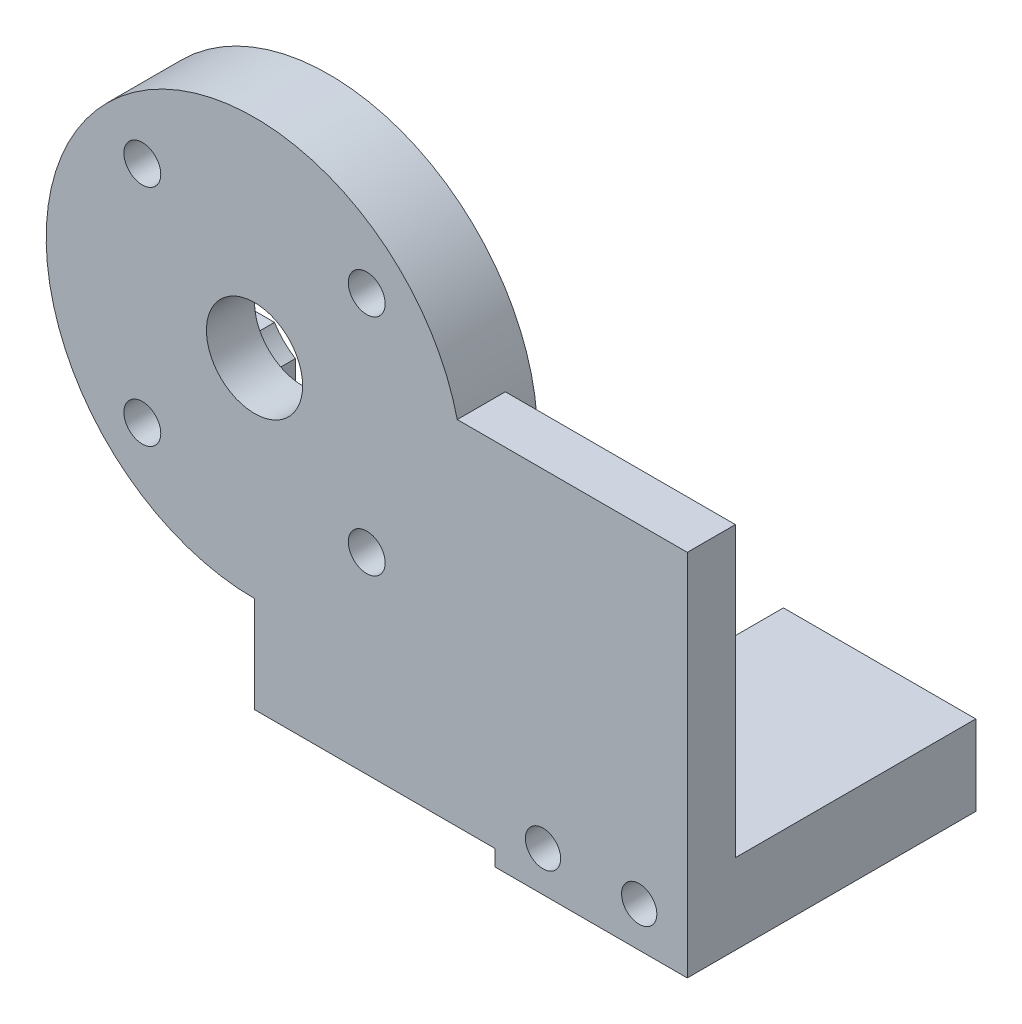
SolidWorks part; units mm, degrees
ref_plane "Front Plane" through (0, 0, 0) normal (0, 0, 1) x (1, 0, 0)
ref_plane "Top Plane" through (0, 0, 0) normal (0, 1, 0) x (1, 0, 0)
ref_plane "Right Plane" through (0, 0, 0) normal (1, 0, 0) x (0, 0, -1)
sketch "Stock_horn_attachment_profile" plane through (0, 0, 0) normal (0, 0, 1) x (1, 0, 0)
  circle A0 centre (0, 0) radius 13
  dimension "D1" = 26
extrude "Stock_horn_attachment" add sketch "Stock_horn_attachment_profile" along normal blind 3 from offset 15
sketch "Finger_arm_profile" plane through (0, 0, 0) normal (0, 0, 1) x (1, 0, 0)
  line L1 (0, -19) -> (27, -19)
  line L2 (0, -19) -> (0, 3)
  line L3 (0, 3) -> (27, 3)
  line L4 (27, -19) -> (27, 3)
  dimension "D1" = 27
  dimension "D2" = 22
extrude "Finger_arm" add sketch "Finger_arm_profile" along normal blind 3 from offset 15
sketch "Descending_contact_finger_profile" plane through (0, 0, 0) normal (0, 0, 1) x (1, 0, 0)
  line L1 (15, -20) -> (27, -20)
  line L2 (15, -20) -> (15, -15)
  line L3 (15, -15) -> (27, -15)
  line L4 (27, -20) -> (27, -15)
  dimension "D1" = 12
  dimension "D2" = 5
extrude "Descending_contact_finger" add sketch "Descending_contact_finger_profile" along normal blind 18
sketch "Horn_center_access_profile" plane through (0, 0, 0) normal (0, 0, 1) x (1, 0, 0)
  circle A0 centre (0, 0) radius 3
  dimension "D1" = 6
extrude "Horn_center_access" cut sketch "Horn_center_access_profile" along normal through all from offset 50
sketch "Captured_horn_key_boss_profile" plane through (0, 0, 0) normal (0, 0, 1) x (1, 0, 0)
  circle A0 centre (0, 0) radius 13
  dimension "D1" = 26
extrude "Captured_horn_key_boss" add sketch "Captured_horn_key_boss_profile" along normal blind 1.65 from offset 13.35
sketch "Stock_horn_pocket_Hub" plane through (0, 0, 0) normal (0, 0, 1) x (1, 0, 0)
  circle A0 centre (0, 0) radius 3.55
  dimension "D1" = 7.1
extrude "Key_pocket_Hub" cut sketch "Stock_horn_pocket_Hub" along normal blind 1.65 from offset 13.35
sketch "Stock_horn_pocket_Horizontal" plane through (0, 0, 0) normal (0, 0, 1) x (1, 0, 0)
  line L1 (-8.15, -2.1) -> (8.15, -2.1)
  line L2 (-8.15, -2.1) -> (-8.15, 2.1)
  line L3 (-8.15, 2.1) -> (8.15, 2.1)
  line L4 (8.15, -2.1) -> (8.15, 2.1)
  dimension "D1" = 16.3
  dimension "D2" = 4.2
extrude "Key_pocket_Horizontal" cut sketch "Stock_horn_pocket_Horizontal" along normal blind 1.65 from offset 13.35
sketch "Stock_horn_pocket_Vertical" plane through (0, 0, 0) normal (0, 0, 1) x (1, 0, 0)
  line L1 (-2.1, -8.15) -> (2.1, -8.15)
  line L2 (-2.1, -8.15) -> (-2.1, 8.15)
  line L3 (-2.1, 8.15) -> (2.1, 8.15)
  line L4 (2.1, -8.15) -> (2.1, 8.15)
  dimension "D1" = 4.2
  dimension "D2" = 16.3
extrude "Key_pocket_Vertical" cut sketch "Stock_horn_pocket_Vertical" along normal blind 1.65 from offset 13.35
sketch "Stock_horn_pocket_Rounded_tips" plane through (0, 0, 0) normal (0, 0, 1) x (1, 0, 0)
  circle A0 centre (8.15, 0) radius 2.1
  circle A1 centre (-8.15, 0) radius 2.1
  circle A2 centre (0, 8.15) radius 2.1
  circle A3 centre (0, -8.15) radius 2.1
  dimension "D1" = 4.2
  dimension "D2" = 4.2
  dimension "D3" = 4.2
  dimension "D4" = 4.2
extrude "Key_pocket_Rounded_tips" cut sketch "Stock_horn_pocket_Rounded_tips" along normal blind 1.65 from offset 13.35
sketch "Unmodified_horn_capture_M2_profile" plane through (0, 0, 0) normal (0, 0, 1) x (1, 0, 0)
  circle A0 centre (7, 7) radius 1.15
  circle A1 centre (-7, 7) radius 1.15
  circle A2 centre (-7, -7) radius 1.15
  circle A3 centre (7, -7) radius 1.15
  dimension "D1" = 2.3
  dimension "D2" = 2.3
  dimension "D3" = 2.3
  dimension "D4" = 2.3
extrude "Unmodified_horn_capture_M2" cut sketch "Unmodified_horn_capture_M2_profile" along normal through all from offset 50
sketch "Horn_center_hub_clearance" plane through (0, 0, 0) normal (0, 0, 1) x (1, 0, 0)
  circle A0 centre (0, 0) radius 4
  dimension "D1" = 8
extrude "Hub_clearance_in_key_boss_only" cut sketch "Horn_center_hub_clearance" along normal blind 1.65 from offset 13.35
sketch "Contact_pad_keeper_profile" plane through (0, 0, 0) normal (0, 0, 1) x (1, 0, 0)
  circle A0 centre (18, -17.5) radius 1.1
  circle A1 centre (24, -17.5) radius 1.1
  dimension "D1" = 2.2
  dimension "D2" = 2.2
extrude "Contact_pad_keeper" cut sketch "Contact_pad_keeper_profile" along normal through all from offset 50
